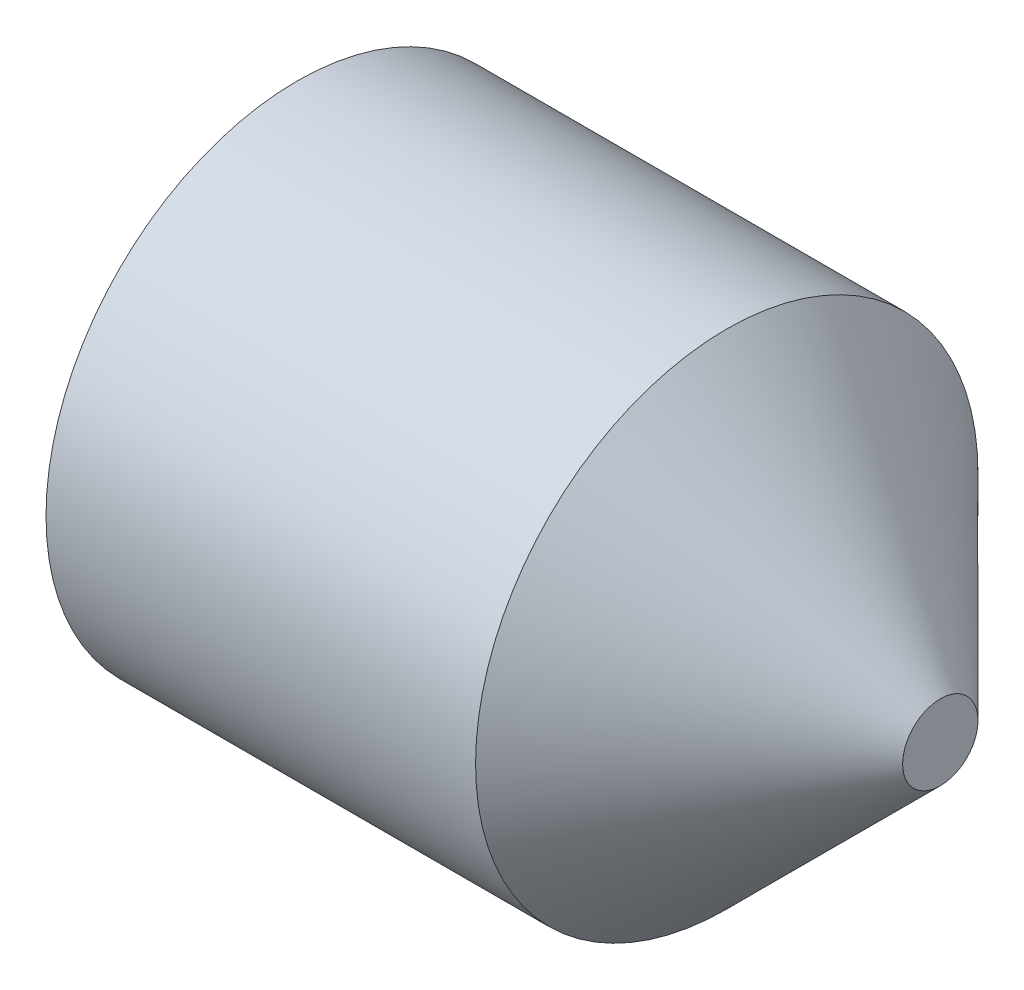
SolidWorks part; units mm, degrees
revolve "BaseBody" add sketch "BodySke" angle 360 about L5
sketch "BodySke" plane through (0, 0, 0) normal (0, 0, 1) x (1, 0, 0)
  line L0 (0, 0) -> (0, 2.4455)
  line L1 (0, 2.4455) -> (0.3201, 3)
  line L2 (0.3201, 3) -> (5.45, 3)
  line L3 (5.45, 3) -> (8, 0.45)
  line L4 (8, 0) -> (0, 0)
  line L5 (-12.7, 0) -> (88.9, 0) construction
  line L6 (8, 0.45) -> (8, 0)
  line L7 (8, 0.45) -> (8, 9.975) construction
  line L8 (0, -2.4455) -> (0.3201, -3) construction
  line L9 (1, 15.875) -> (1, -3.175) construction
  line L10 (5.45, -3) -> (8, -0.45) construction
  dimension "Diameter" = 6
  dimension "Drive_ch_ang" = 60
  dimension "Minor_dia" = 4.891
  dimension "Tip_dia" = 0.9
  dimension "Length" = 8
  dimension "Advance" = 1
  dimension "Cone_ang" = 90
cosmetic thread "ThreadCosmetic" [suppressed] parameters "Thread_minor"=4.891
material "Stahl verzinkt"
ref_plane "Plane1" through (0, 0, 0) normal (0, 0, 1) x (1, 0, 0)
ref_plane "Plane2" through (0, 0, 0) normal (0, 1, 0) x (1, 0, 0)
ref_plane "Plane3" through (0, 0, 0) normal (1, 0, 0) x (0, 0, -1)
sketch "Sketch2" plane through (0, 0, 0) normal (-1, 0, 0) x (0, 0, 1)
  line L0 (0.866, 1.5) -> (-0.866, 1.5)
  line L1 (-0.866, 1.5) -> (-1.7321, 0)
  line L2 (0.866, 1.5) -> (1.7321, 0)
  line L3 (0.866, -1.5) -> (1.7321, 0)
  line L4 (0.866, -1.5) -> (-0.866, -1.5)
  line L5 (-0.866, -1.5) -> (-1.7321, 0)
  dimension "Hex_size" = 3
  dimension "D2" = 1.5
  dimension "D3" = 1.5
extrude "Hex" cut sketch "Sketch2" against normal blind 3.5
sketch "ThdSchSke" [suppressed] plane through (0, 0, 0) normal (0, 0, 1) x (1, 0, 0)
  line L0 (0.9515, -10.352) -> (-0.2025, -12)
  line L1 (0.9515, -10.352) -> (2.1054, -12)
  line L2 (2.1054, -12) -> (2.1054, -15)
  line L3 (-3.175, 0) -> (5.1513, 0) construction
  line L5 (2.1054, -15) -> (-0.2025, -15)
  line L6 (-0.2025, -15) -> (-0.2025, -12)
  line L8 (0.9515, 12) -> (0.9515, -12) construction
  dimension "Thread_minor" = 4.891
  dimension "Diameter" = 6
revolve "ThreadSchematic" [suppressed] cut sketch "ThdSchSke" angle 360 about L3
pattern_linear "ThdSchPat" [suppressed]
equation "\"D2@Sketch2\" = \"Hex_size@Sketch2\" / 2"
equation "\"D3@Sketch2\" = \"Hex_size@Sketch2\" / 2"
equation "\"Thread_minor@ThreadCosmetic\" = \"Minor_dia@BodySke\""
equation "\"Thread_minor@ThdSchSke\" = \"Thread_minor@ThreadCosmetic\""
equation "\"Diameter@ThdSchSke\" = \"Diameter@BodySke\""
equation "\"Overcut@ThdSchSke\" = \"Diameter@BodySke\" * 1.25"
equation "\"Num_threads@ThdSchPat\" = int( (\"Length@BodySke\" - ( ( ( \"Diameter@BodySke\" - \"Minor_dia@BodySke\" ) * 0.5 ) / tan( \"Drive_ch_ang@BodySke\" * 0.017453292 ) ) - ( ( ( \"Diameter@BodySke\" - \"Tip_dia@BodySke\" ) * 0.5 ) / tan( \"Cone_ang@BodySke\" / 2.0 * 0.017453292 ) ) ) / \"Advance@BodySke\" + 0.999 )  + 1"
equation "\"Advance@ThdSchPat\" = (\"Length@BodySke\" - ( ( ( \"Diameter@BodySke\" - \"Minor_dia@BodySke\" ) * 0.5 ) / tan( \"Drive_ch_ang@BodySke\" * 0.017453292 ) ) - ( ( ( \"Diameter@BodySke\" - \"Tip_dia@BodySke\" ) * 0.5 ) / tan( \"Cone_ang@BodySke\" / 2.0 * 0.017453292 ) ) ) /  (\"Num_threads@ThdSchPat\" - 1) 'relax it"
equation "' \"Num_threads@ThdSchPat\" = \"Num_threads@ThdSchPat\" - sgn( \"Num_threads@ThdSchPat\" - 1) '---chamfered tips only---"
